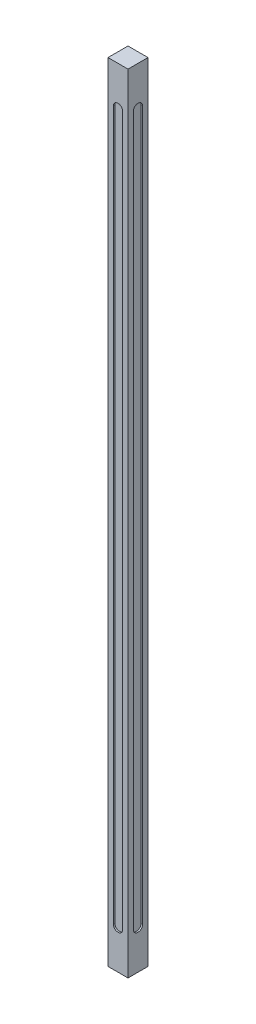
SolidWorks part; units mm, degrees
ref_plane "Front Plane" through (0, 0, 0) normal (0, 0, 1) x (1, 0, 0)
ref_plane "Top Plane" through (0, 0, 0) normal (0, 1, 0) x (1, 0, 0)
ref_plane "Right Plane" through (0, 0, 0) normal (1, 0, 0) x (0, 0, -1)
sketch "Sketch1" plane through (0, 0, 0) normal (0, 1, 0) x (1, 0, 0)
  line L1 (12.7, -12.7) -> (-12.7, -12.7)
  line L2 (12.7, -12.7) -> (12.7, 12.7)
  line L3 (12.7, 12.7) -> (-12.7, 12.7)
  line L4 (-12.7, -12.7) -> (-12.7, 12.7)
  line L5 (12.7, -12.7) -> (-12.7, 12.7) construction
  line L6 (12.7, 12.7) -> (-12.7, -12.7) construction
  point P0 (0, 0)
  dimension "D1" = 25.4
extrude "Boss-Extrude1" add sketch "Sketch1" along normal mid plane 1000
sketch "Sketch5" plane through (0, 0, 12.7) normal (0, 0, 1) x (1, 0, 0)
  line L0 (0, 450) -> (0, -450) construction
  line L1 (6, 450) -> (6, -450)
  line L2 (-6, 450) -> (-6, -450)
  arc A0 (6, 450) -> (-6, 450) centre (0, 450) ccw
  arc A1 (-6, -450) -> (6, -450) centre (0, -450) ccw
  point P2 (0, 0)
  dimension "D1" = 6
  dimension "D2" = 900
extrude "Cut-Extrude2" cut sketch "Sketch5" against normal blind 2
sketch "Sketch6" plane through (12.7, 0, 0) normal (1, 0, 0) x (0, 0, -1)
  line L0 (0, 450) -> (0, -450) construction
  line L1 (6, 450) -> (6, -450)
  line L2 (-6, 450) -> (-6, -450)
  arc A0 (6, 450) -> (-6, 450) centre (0, 450) ccw
  arc A1 (-6, -450) -> (6, -450) centre (0, -450) ccw
  point P2 (0, 0)
  dimension "D2" = 6
  dimension "D1" = 900
extrude "Cut-Extrude3" cut sketch "Sketch6" against normal blind 2
sketch "Sketch8" plane through (0, 0, -12.7) normal (0, 0, -1) x (-1, 0, 0)
  line L0 (0, 450) -> (0, -450) construction
  line L1 (6, 450) -> (6, -450)
  line L2 (-6, 450) -> (-6, -450)
  arc A0 (6, 450) -> (-6, 450) centre (0, 450) ccw
  arc A1 (-6, -450) -> (6, -450) centre (0, -450) ccw
  point P2 (0, 0)
  dimension "D2" = 6
  dimension "D1" = 900
extrude "Cut-Extrude4" cut sketch "Sketch8" against normal blind 2
sketch "Sketch9" plane through (-12.7, 0, 0) normal (-1, 0, 0) x (0, 0, 1)
  line L0 (0, 450) -> (0, -450) construction
  line L1 (6, 450) -> (6, -450)
  line L2 (-6, 450) -> (-6, -450)
  arc A0 (6, 450) -> (-6, 450) centre (0, 450) ccw
  arc A1 (-6, -450) -> (6, -450) centre (0, -450) ccw
  point P2 (0, 0)
  dimension "D2" = 6
  dimension "D1" = 900
extrude "Cut-Extrude5" cut sketch "Sketch9" against normal blind 2
